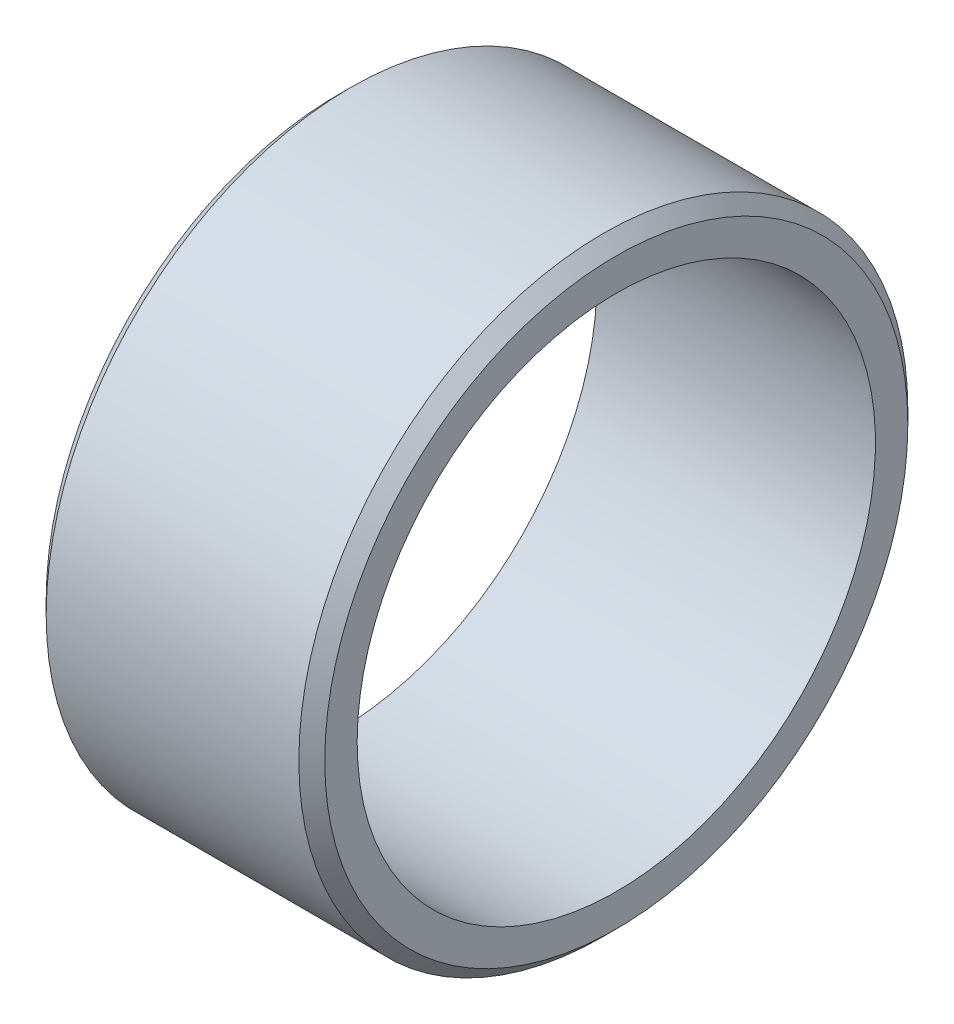
SolidWorks part; units mm, degrees
material "Acier non allié"
ref_plane "Plan de face" through (0, 0, 0) normal (0, 0, 1) x (1, 0, 0)
ref_plane "Plan de dessus" through (0, 0, 0) normal (0, 1, 0) x (1, 0, 0)
ref_plane "Plan de droite" through (0, 0, 0) normal (1, 0, 0) x (0, 0, -1)
sketch "Esquisse1" plane through (0, 0, 0) normal (0, 0, 1) x (1, 0, 0)
  line L0 (-20.6639, 0) -> (23.215, 0) construction
  line L1 (-1, 23.5) -> (0, 22.5)
  line L2 (-20.5, 23.5) -> (-1, 23.5)
  line L3 (-21.5, 22.5) -> (-21.5, 20)
  line L4 (-21.5, 20) -> (0, 20)
  line L5 (0, 22.5) -> (0, 20)
  line L6 (-21.5, 22.5) -> (-20.5, 23.5)
  point P3 (-21.5, 23.5)
  point P6 (0, 23.5)
  dimension "D1" = 40
  dimension "D2" = 47
  dimension "D3" = 21.5
  dimension "D4" = 1
  dimension "D5" = 45
  dimension "D6" = 1
  dimension "D7" = 45
revolve "Révolution1" add sketch "Esquisse1" angle 360 about L0
